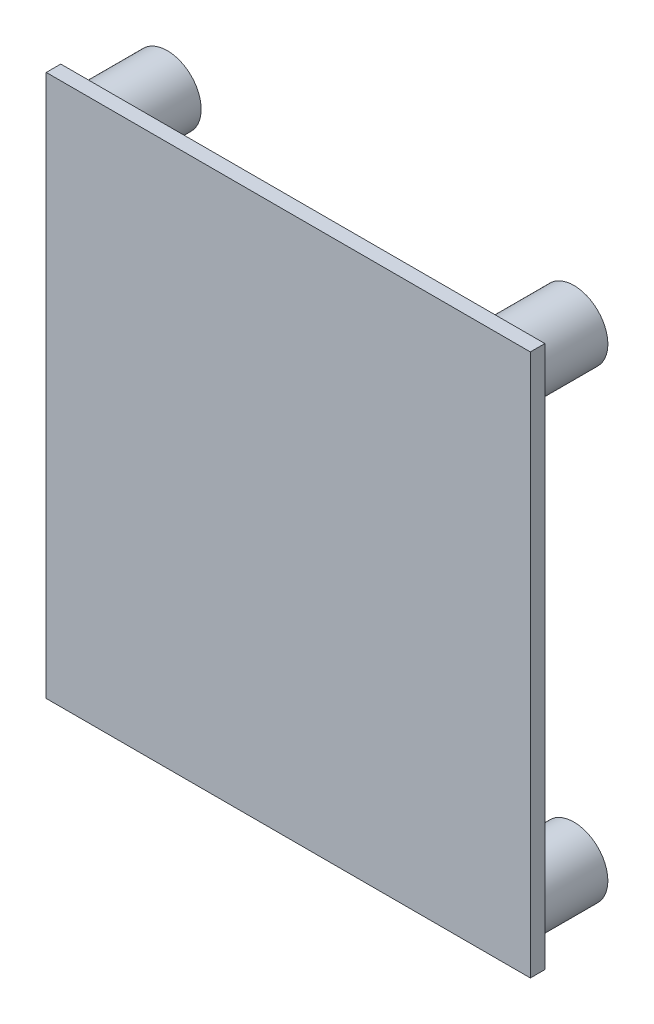
SolidWorks part; units mm, degrees
ref_plane "Спереди" through (0, 0, 0) normal (0, 0, 1) x (1, 0, 0)
ref_plane "Сверху" through (0, 0, 0) normal (0, 1, 0) x (1, 0, 0)
ref_plane "Справа" through (0, 0, 0) normal (1, 0, 0) x (0, 0, -1)
sketch "Эскиз1" plane through (0, 0, 0) normal (0, 0, 1) x (1, 0, 0)
  line L1 (0, 0) -> (50, 0)
  line L2 (0, 0) -> (0, 56)
  line L3 (0, 56) -> (50, 56)
  line L4 (50, 0) -> (50, 56)
  dimension "D1" = 56
  dimension "D2" = 50
extrude "Бобышка-Вытянуть1" add sketch "Эскиз1" along normal blind 1.5
sketch "Эскиз2" plane through (0, 0, 0) normal (0, 0, -1) x (-1, 0, 0)
  line L0 (-46, 52.2) -> (-46, 4.2) construction
  line L1 (-4, 52.2) -> (-4, 4.2) construction
  line L2 (-46, 52.2) -> (-4, 52.2) construction
  line L3 (-46, 4.2) -> (-4, 4.2) construction
  line L4 (-4, 52.2) -> (-4, 56) construction
  line L5 (-50, 56) -> (0, 56) construction
  line L6 (-4, 56) -> (-4, 52.2) construction
  line L7 (-4, 52.2) -> (0, 52.2) construction
  line L8 (0, 56) -> (0, 0) construction
  circle A0 centre (-46, 4.2) radius 1.5
  circle A1 centre (-4, 4.2) radius 1.5
  circle A2 centre (-4, 52.2) radius 1.5
  circle A3 centre (-46, 52.2) radius 1.5
  circle A4 centre (-46, 52.2) radius 3.5
  circle A5 centre (-4, 52.2) radius 3.5
  circle A6 centre (-46, 4.2) radius 3.5
  circle A7 centre (-4, 4.2) radius 3.5
  point P17 (0, 0)
  point P19 (-47.5, 4.2)
  point P21 (-2.5, 4.2)
  dimension "D1" = 3
  dimension "D6" = 7
  dimension "D2" = 48
  dimension "D3" = 42
  dimension "D4" = 3.8
  dimension "D5" = 4
extrude "Бобышка-Вытянуть2" add sketch "Эскиз2" along normal blind 7
